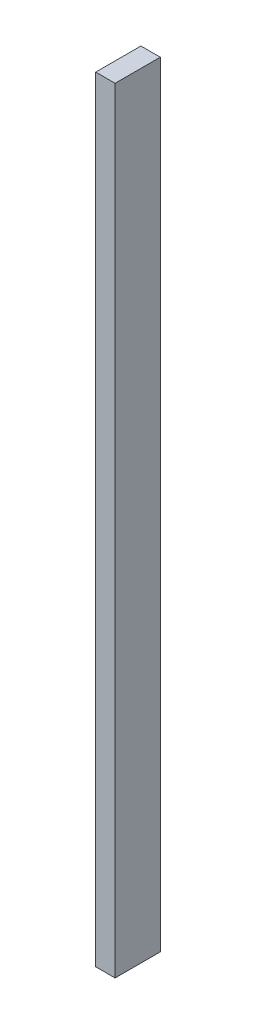
SolidWorks part; units mm, degrees
ref_plane "Front Plane" through (0, 0, 0) normal (0, 0, 1) x (1, 0, 0)
ref_plane "Top Plane" through (0, 0, 0) normal (0, 1, 0) x (1, 0, 0)
ref_plane "Right Plane" through (0, 0, 0) normal (1, 0, 0) x (0, 0, -1)
sketch "Sketch1" plane through (0, 0, 0) normal (0, 1, 0) x (1, 0, 0)
  line L1 (19.05, -44.45) -> (-19.05, -44.45)
  line L2 (19.05, -44.45) -> (19.05, 44.45)
  line L3 (19.05, 44.45) -> (-19.05, 44.45)
  line L4 (-19.05, -44.45) -> (-19.05, 44.45)
  line L5 (19.05, -44.45) -> (-19.05, 44.45) construction
  line L6 (19.05, 44.45) -> (-19.05, -44.45) construction
  point P0 (0, 0)
  dimension "D1" = 38.1
  dimension "D2" = 88.9
extrude "Boss-Extrude1" add sketch "Sketch1" along normal mid plane 1524
